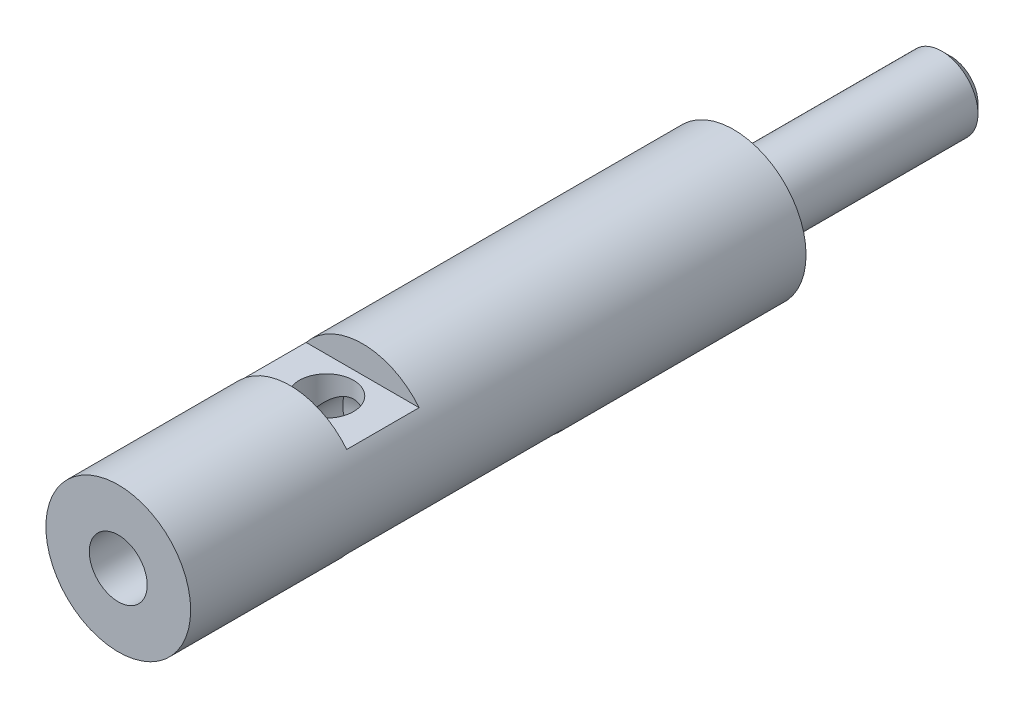
SolidWorks part; units mm, degrees
ref_plane "Front Plane" through (0, 0, 0) normal (0, 0, 1) x (1, 0, 0)
ref_plane "Top Plane" through (0, 0, 0) normal (0, 1, 0) x (1, 0, 0)
ref_plane "Right Plane" through (0, 0, 0) normal (1, 0, 0) x (0, 0, -1)
sketch "Sketch1" plane through (0, 0, 0) normal (0, 0, 1) x (1, 0, 0)
  circle A0 centre (0, 0) radius 4
  dimension "D1" = 8
extrude "Boss-Extrude1" add sketch "Sketch1" against normal blind 34
sketch "Sketch2" plane through (0, 0, -34) normal (0, 0, -1) x (-1, 0, 0)
  circle A0 centre (0, 0) radius 2
  dimension "D1" = 4
extrude "Boss-Extrude2" add sketch "Sketch2" along normal blind 12
chamfer "Chamfer1" distance 0.5 angle 45 1 edges at (-2, 0, -46)
hole_wizard "Ø3.2 (3.2) Diameter Hole1" positions "Sketch3" profile "Sketch4" hole size "Ø3.2" standard "ANSI Metric"
sketch "Sketch3" plane through (0, 0, 0) normal (0, 0, 1) x (1, 0, 0)
  point P0 (0, 0)
sketch "Sketch4" plane through (0, 0, 0) normal (1, 0, 0) x (0, -1, 0)
  line L0 (0, 0) -> (0, 14.9614)
  line L1 (0, 14.9614) -> (1.6, 14)
  line L2 (1.6, 14) -> (1.6, 0)
  line L5 (1.6, 0) -> (0, 0)
  line L10 (0, 14.9614) -> (-1.6, 14) construction
  line L11 (0, -6.35) -> (0, 107.95) construction
  dimension "Hole Dia." = 3.2
  dimension "Hole Depth" = 14
  dimension "Drill Angle" = 118
sketch "Sketch5" plane through (0, 0, 0) normal (1, 0, 0) x (0, 0, -1)
  line L0 (0, -4) -> (34, -4) construction
  line L1 (9.5, -4) -> (21.5, -4)
  line L2 (9.5, -4) -> (9.5, -2.5)
  line L3 (9.5, -2.5) -> (21.5, -2.5)
  line L4 (21.5, -4) -> (21.5, -2.5)
  line L5 (34, 4) -> (0, 4) construction
  line L6 (0, 4) -> (0, -4) construction
  line L7 (9.5, 4) -> (13.5, 4)
  line L8 (9.5, 4) -> (9.5, 2.5)
  line L9 (9.5, 2.5) -> (13.5, 2.5)
  line L10 (13.5, 4) -> (13.5, 2.5)
  dimension "D1" = 1.5
  dimension "D2" = 12
  dimension "D3" = 1.5
  dimension "D4" = 4
  dimension "D5" = 9.5
extrude "Cut-Extrude1" cut sketch "Sketch5" against normal through all both and the other way through all
hole_wizard "Ø3.0 (3) Diameter Hole1" positions "Sketch6" profile "Sketch7" hole size "Ø3.0" standard "ANSI Metric"
sketch "Sketch6" plane through (0, 2.5, 0) normal (0, 1, 0) x (1, 0, 0)
  line L0 (-3.1225, 9.5) -> (3.1225, 13.5) construction
  point P7 (0, 11.5)
sketch "Sketch7" plane through (0, 2.5, -11.5) normal (1, 0, 0) x (0, 0, 1)
  line L0 (0, 0) -> (0, 0.9)
  line L1 (0, 0.9) -> (1.5, 0.9)
  line L2 (1.5, 0.9) -> (1.5, 0)
  line L5 (1.5, 0) -> (0, 0)
  line L11 (0, -6.35) -> (0, 107.95) construction
  dimension "Thru Hole Dia." = 3
  dimension "Thru Hole Depth" = 0.9
